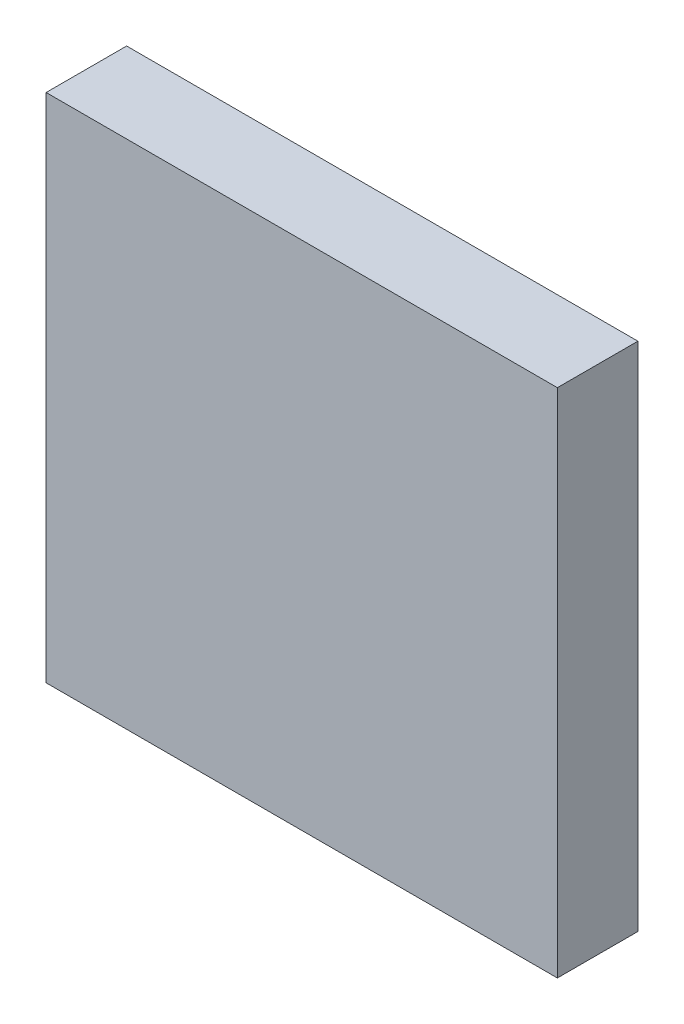
SolidWorks part; units mm, degrees
ref_plane "Front Plane" through (0, 0, 0) normal (0, 0, 1) x (1, 0, 0)
ref_plane "Top Plane" through (0, 0, 0) normal (0, 1, 0) x (1, 0, 0)
ref_plane "Right Plane" through (0, 0, 0) normal (1, 0, 0) x (0, 0, -1)
sketch "Sketch1" plane through (0, 0, 0) normal (0, 0, 1) x (1, 0, 0)
  line L4 (31.75, 31.75) -> (-31.75, -31.75) construction
  line L8 (-31.75, 31.75) -> (-31.75, -31.75)
  line L9 (-31.75, -31.75) -> (31.75, -31.75)
  line L10 (31.75, -31.75) -> (31.75, 31.75)
  line L11 (31.75, 31.75) -> (-31.75, 31.75)
  point P2 (0, 0)
  point P4 (0, 0)
  point P6 (0, 0)
  point P7 (0, 0)
  dimension "D1" = 63.5
extrude "Boss-Extrude1" add sketch "Sketch1" along normal blind 10
